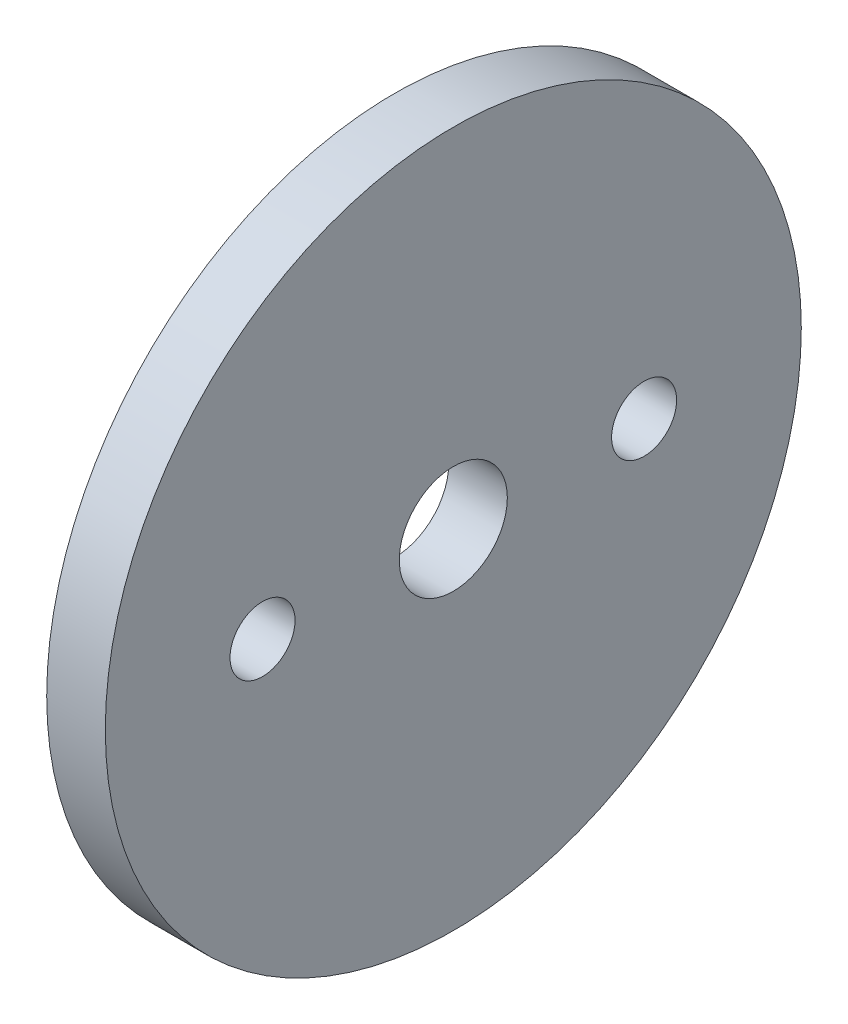
SolidWorks part; units mm, degrees
material "Wildman Fiberglass"
ref_plane "Front Plane" through (0, 0, 0) normal (0, 0, 1) x (1, 0, 0)
ref_plane "Top Plane" through (0, 0, 0) normal (0, 1, 0) x (1, 0, 0)
ref_plane "Right Plane" through (0, 0, 0) normal (1, 0, 0) x (0, 0, -1)
sketch "Sketch1" plane through (0, 0, 0) normal (1, 0, 0) x (0, 0, -1)
  circle A0 centre (0, 0) radius 14.478
  dimension "D1" = 28.956
extrude "Boss-Extrude1" add sketch "Sketch1" along normal blind 2.4384
hole_wizard "#8 Threaded Rod Clearance" positions "Sketch3" profile "Sketch4" hole size "#8" standard "ANSI Inch" end condition through all
sketch "Sketch3" plane through (2.4384, 0, 0) normal (1, 0, 0) x (0, 0, -1)
  point P0 (0, 0)
sketch "Sketch4" plane through (2.4384, 0, 0) normal (0, 1, 0) x (0, 0, -1)
  line L0 (0, 0) -> (0, 2.4384)
  line L1 (0, 2.4384) -> (2.2479, 2.4384)
  line L2 (2.2479, 2.4384) -> (2.2479, 0)
  line L5 (2.2479, 0) -> (0, 0)
  line L11 (0, -6.35) -> (0, 107.95) construction
  dimension "Thru Hole Dia." = 4.4958
  dimension "Thru Hole Depth" = 2.4384
hole_wizard "Ejection Charge Passthrough" positions "Sketch5" profile "Sketch6" hole size "#36" standard "ANSI Inch" end condition through all
sketch "Sketch5" plane through (2.4384, 0, 0) normal (1, 0, 0) x (0, 0, -1)
  line L0 (-7.9375, 0) -> (7.9375, 0) construction
  point P0 (-7.9375, 0)
  point P2 (7.9375, 0)
  point P7 (0, 0)
  dimension "D1" = 15.875
sketch "Sketch6" plane through (2.4384, 0, 7.9375) normal (0, 1, 0) x (0, 0, -1)
  line L0 (0, 0) -> (0, 2.4384)
  line L1 (0, 2.4384) -> (1.3525, 2.4384)
  line L2 (1.3525, 2.4384) -> (1.3525, 0)
  line L5 (1.3525, 0) -> (0, 0)
  line L11 (0, -6.35) -> (0, 107.95) construction
  dimension "Thru Hole Dia." = 2.7051
  dimension "Thru Hole Depth" = 2.4384
